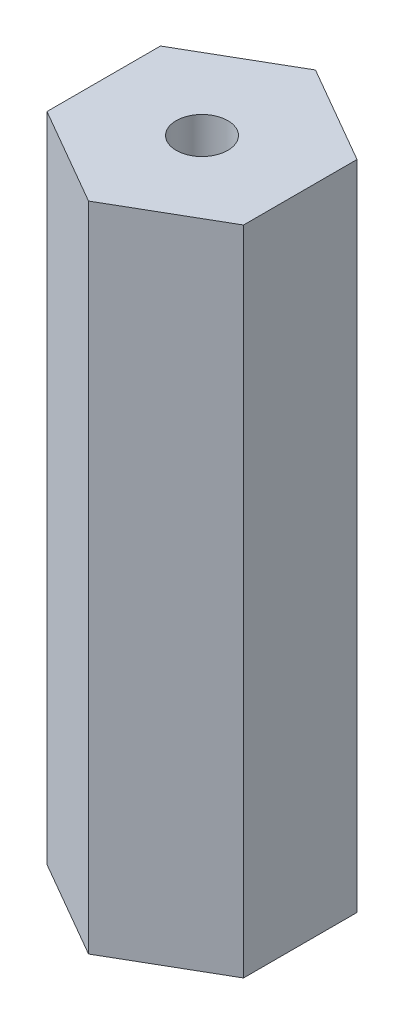
SolidWorks part; units mm, degrees
material "6061-T6 (SS)"
ref_plane "Front Plane" through (0, 0, 0) normal (0, 0, 1) x (1, 0, 0)
ref_plane "Top Plane" through (0, 0, 0) normal (0, 1, 0) x (1, 0, 0)
ref_plane "Right Plane" through (0, 0, 0) normal (1, 0, 0) x (0, 0, -1)
sketch "Sketch1" plane through (0, 0, 0) normal (0, 1, 0) x (1, 0, 0)
  line L1 (2.2606, 1.3052) -> (0, 2.6103)
  line L2 (0, 2.6103) -> (-2.2606, 1.3052)
  line L3 (-2.2606, 1.3052) -> (-2.2606, -1.3052)
  line L4 (-2.2606, -1.3052) -> (0, -2.6103)
  line L5 (0, -2.6103) -> (2.2606, -1.3052)
  line L6 (2.2606, -1.3052) -> (2.2606, 1.3052)
  circle A0 centre (0, 0) radius 2.2606 construction
  dimension "D1" = 4.5212
extrude "Boss-Extrude1" add sketch "Sketch1" along normal blind 15
sketch "Sketch2" plane through (0, 0, 0) normal (0, -1, 0) x (1, 0, 0)
  circle A0 centre (0, 0) radius 1.4732
  dimension "D1" = 2.9464
sketch "Sketch3" plane through (0, 15, 0) normal (0, 1, 0) x (1, 0, 0)
  circle A0 centre (0, 0) radius 0.5937
extrude "Cut-Extrude1" cut sketch "Sketch3" against normal through all
